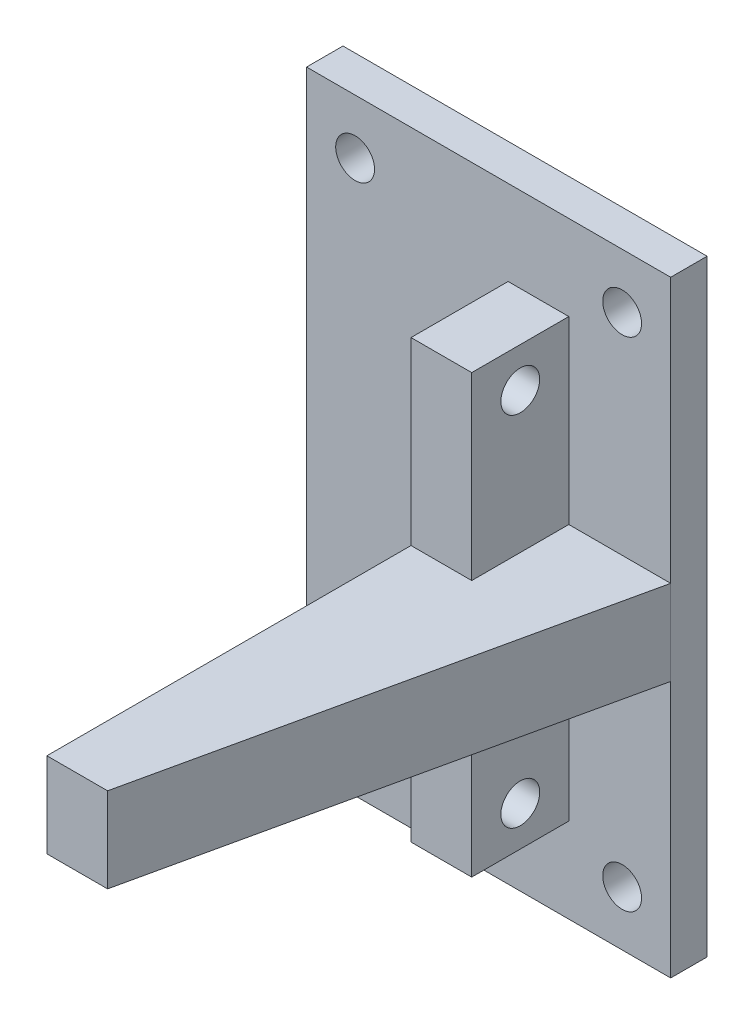
SolidWorks part; units mm, degrees
ref_plane "前视基准面" through (0, 0, 0) normal (0, 0, 1) x (1, 0, 0)
ref_plane "上视基准面" through (0, 0, 0) normal (0, 1, 0) x (1, 0, 0)
ref_plane "右视基准面" through (0, 0, 0) normal (1, 0, 0) x (0, 0, -1)
other "Configuration Table"
sketch "草图1" plane through (0, 0, 0) normal (0, 0, 1) x (1, 0, 0)
  line L1 (-10, 10) -> (-40, 10)
  line L2 (-10, 10) -> (-10, -40)
  line L3 (-10, -40) -> (-40, -40)
  line L4 (-40, 10) -> (-40, -40)
  circle A0 centre (-14, 5.5) radius 1.6
  circle A1 centre (-36, -35.5) radius 1.6
  circle A2 centre (-14, -35.5) radius 1.6
  circle A3 centre (-36, 5.5) radius 1.6
extrude "凸台-拉伸1" add sketch "草图1" along normal blind 3
sketch "草图2" plane through (0, 0, 3) normal (0, 0, 1) x (1, 0, 0)
  line L0 (-10, -15) -> (-40, -15) construction
  line L1 (-10, -40) -> (-10, 10) construction
  line L2 (-40, 10) -> (-40, -40) construction
  line L4 (-18.3942, 3) -> (-23.3942, 3)
  line L5 (-18.3942, 3) -> (-18.3942, -33)
  line L6 (-18.3942, -33) -> (-23.3942, -33)
  line L7 (-23.3942, 3) -> (-23.3942, -33)
  line L8 (-18.3942, 3) -> (-23.3942, -33) construction
  line L9 (-18.3942, -33) -> (-23.3942, 3) construction
  point P6 (-20.8942, -15)
  dimension "D1" = 5
  dimension "D2" = 36
extrude "凸台-拉伸2" add sketch "草图2" along normal blind 8
sketch "草图5" plane through (-18.3942, 0, 0) normal (1, 0, 0) x (0, 0, -1)
  line L0 (-7, 3) -> (-7, -33) construction
  line L1 (-11, 3) -> (-3, 3) construction
  line L2 (-11, -33) -> (-3, -33) construction
  circle A0 centre (-7, -0.268) radius 1.6
  circle A1 centre (-7, -29.732) radius 1.6
  point P10 (-7, -15)
  dimension "D3" = 3.2
  dimension "D4" = 3.2
  dimension "D1" = 14.732
  dimension "D2" = 14.732
extrude "切除-拉伸1" cut sketch "草图5" against normal blind 10
sketch "草图6" plane through (0, 0, 11) normal (0, 0, 1) x (1, 0, 0)
  line L0 (-18.3942, -15.34) -> (-23.3942, -15.34) construction
  line L1 (-18.3942, -33) -> (-18.3942, 3) construction
  line L2 (-23.3942, 3) -> (-23.3942, -33) construction
  line L4 (-18.3942, -11.84) -> (-23.3942, -11.84)
  line L5 (-18.3942, -11.84) -> (-18.3942, -18.84)
  line L6 (-18.3942, -18.84) -> (-23.3942, -18.84)
  line L7 (-23.3942, -11.84) -> (-23.3942, -18.84)
  line L8 (-18.3942, -11.84) -> (-23.3942, -18.84) construction
  line L9 (-18.3942, -18.84) -> (-23.3942, -11.84) construction
  point P6 (-20.8942, -15.34)
  dimension "D1" = 7
extrude "凸台-拉伸3" add sketch "草图6" along normal blind 30
sketch "草图7" plane through (0, -11.84, 0) normal (0, 1, 0) x (1, 0, 0)
  line L0 (-18.3942, -41) -> (-10, -3)
rib "筋1" sketch "草图7" sketch "草图7" thickness 7 extrusion direction parallel to sketch draft on no parameters "D1"=7
